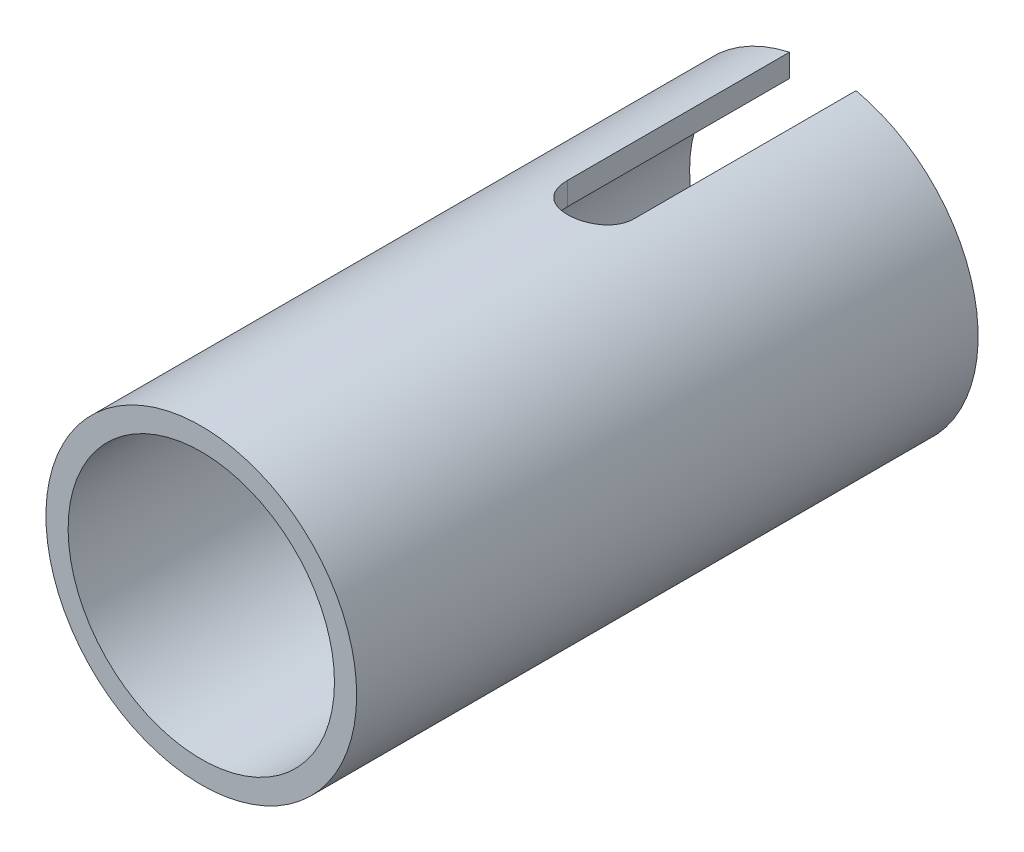
SolidWorks part; units mm, degrees
material "2.0060 (Cu-ETP)"
ref_plane "Plan de face" through (0, 0, 0) normal (0, 0, 1) x (1, 0, 0)
ref_plane "Plan de dessus" through (0, 0, 0) normal (0, 1, 0) x (1, 0, 0)
ref_plane "Plan de droite" through (0, 0, 0) normal (1, 0, 0) x (0, 0, -1)
sketch "Esquisse1" plane through (0, 0, 0) normal (0, 0, 1) x (1, 0, 0)
  circle A0 centre (0, 0) radius 6
  circle A1 centre (0, 0) radius 7
  dimension "D1" = 12
  dimension "D2" = 1
extrude "Boss.-Extru.1" add sketch "Esquisse1" along normal mid plane 28
sketch "Esquisse2" plane through (0, 0, 0) normal (0, 1, 0) x (1, 0, 0)
  line L0 (-1.5, 14) -> (-1.5, 4)
  line L1 (7, 14) -> (-7, 14) construction
  line L2 (0, 0) -> (0, 14) construction
  line L4 (1.5, 14) -> (1.5, 4)
  arc A0 (-1.5, 4) -> (1.5, 4) centre (0, 4) ccw
  dimension "D3" = 1.5
  dimension "D1" = 1.5
  dimension "D2" = 10
extrude "Enlèv. mat.-Extru.1" cut sketch "Esquisse2" along normal through all flip side to cut
